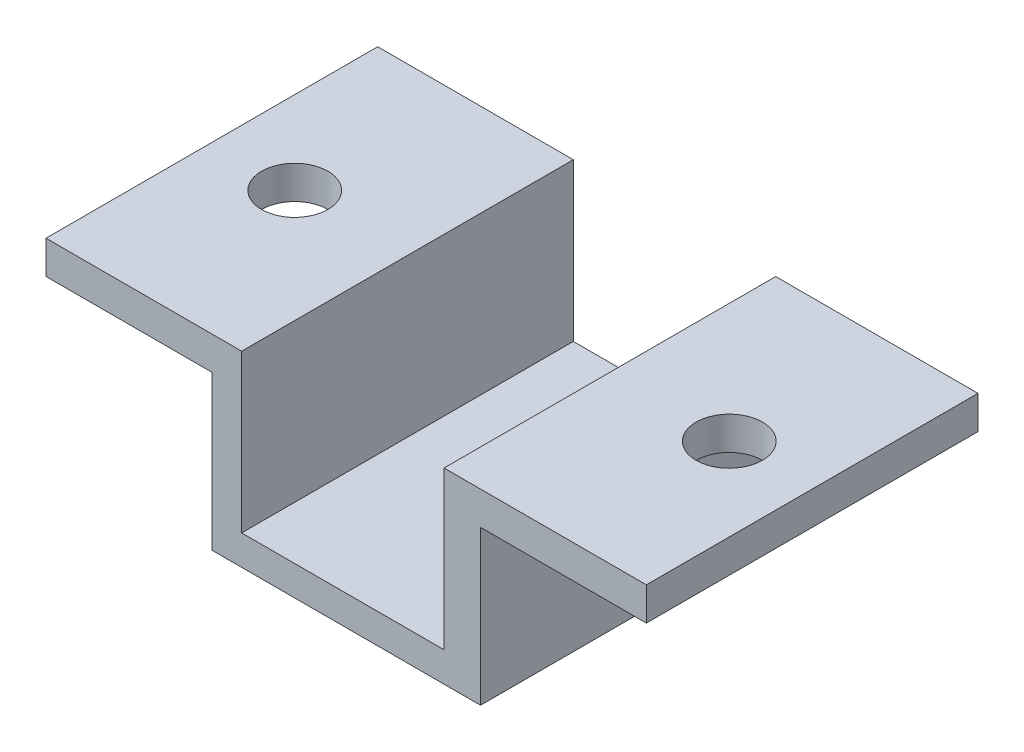
SolidWorks part; units mm, degrees
ref_plane "Front Plane" through (0, 0, 0) normal (0, 0, 1) x (1, 0, 0)
ref_plane "Top Plane" through (0, 0, 0) normal (0, 1, 0) x (1, 0, 0)
ref_plane "Right Plane" through (0, 0, 0) normal (1, 0, 0) x (0, 0, -1)
sketch "Sketch2" plane through (0, 0, 0) normal (0, 1, 0) x (1, 0, 0)
  line L1 (0, 0) -> (45.98, 0)
  line L2 (0, 0) -> (0, 25.4)
  line L3 (0, 25.4) -> (45.98, 25.4)
  line L4 (45.98, 0) -> (45.98, 25.4)
  dimension "D1" = 25.4
  dimension "D2" = 45.98
extrude "Boss-Extrude1" add sketch "Sketch2" along normal blind 14.34
sketch "Sketch3" plane through (0, 14.34, 0) normal (0, 1, 0) x (1, 0, 0)
  line L0 (0, 0) -> (45.98, 0) construction
  line L1 (14.986, 0) -> (30.486, 0)
  line L2 (14.986, 0) -> (14.986, 25.4)
  line L3 (14.986, 25.4) -> (30.486, 25.4)
  line L4 (30.486, 0) -> (30.486, 25.4)
  line L5 (45.98, 25.4) -> (0, 25.4) construction
  line L6 (0, 25.4) -> (0, 0) construction
  dimension "D1" = 15.5
  dimension "D2" = 12.7
extrude "Cut-Extrude1" cut sketch "Sketch3" against normal blind 12.054
sketch "Sketch4" plane through (0, 0, 0) normal (0, -1, 0) x (-1, 0, 0)
  line L0 (-45.98, 25.4) -> (0, 25.4) construction
  line L1 (0, 0) -> (-12.7, 0)
  line L2 (0, 0) -> (0, 25.4)
  line L3 (0, 25.4) -> (-12.7, 25.4)
  line L4 (-12.7, 0) -> (-12.7, 25.4)
  dimension "D1" = 12.7
extrude "Cut-Extrude2" cut sketch "Sketch4" against normal blind 11.8
sketch "Sketch5" plane through (0, 0, 0) normal (0, -1, 0) x (-1, 0, 0)
  line L0 (-45.98, 25.4) -> (-12.7, 25.4) construction
  line L1 (-45.98, 0) -> (-33.28, 0)
  line L2 (-45.98, 0) -> (-45.98, 25.4)
  line L3 (-45.98, 25.4) -> (-33.28, 25.4)
  line L4 (-33.28, 0) -> (-33.28, 25.4)
  dimension "D1" = 12.7
extrude "Cut-Extrude3" cut sketch "Sketch5" against normal blind 11.8
sketch "Sketch6" plane through (0, 11.8, 0) normal (0, -1, 0) x (-1, 0, 0)
  line L0 (-12.7, 0) -> (0, 0) construction
  line L1 (0, 0) -> (0, 25.4) construction
  circle A0 centre (-6.35, 12.7) radius 2.54
  point P6 (0, 12.7)
  dimension "D1" = 12.7
  dimension "D2" = 6.35
extrude "Cut-Extrude4" cut sketch "Sketch6" against normal blind 2.54
sketch "Sketch7" plane through (0, 11.8, 0) normal (0, -1, 0) x (-1, 0, 0)
  line L0 (-45.98, 0) -> (-33.28, 0) construction
  line L1 (-45.98, 25.4) -> (-45.98, 0) construction
  circle A0 centre (-39.63, 12.7) radius 2.54
  dimension "D1" = 12.7
  dimension "D2" = 6.35
extrude "Cut-Extrude5" cut sketch "Sketch7" against normal blind 2.54
